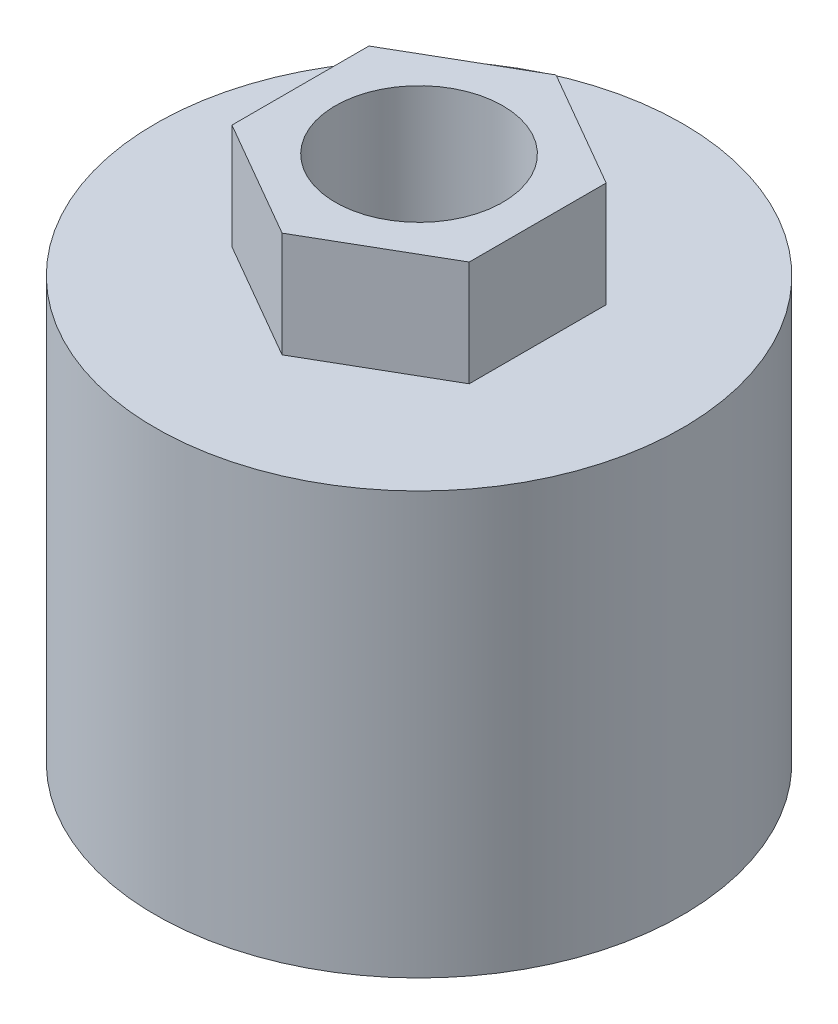
SolidWorks part; units mm, degrees
ref_plane "Front Plane" through (0, 0, 0) normal (0, 0, 1) x (1, 0, 0)
ref_plane "Top Plane" through (0, 0, 0) normal (0, 1, 0) x (1, 0, 0)
ref_plane "Right Plane" through (0, 0, 0) normal (1, 0, 0) x (0, 0, -1)
sketch "Sketch1" plane through (0, 0, 0) normal (0, 0, 1) x (1, 0, 0)
  line L3 (15.875, 0) -> (15.875, 25.4)
  line L7 (0, 0) -> (0, 63.6042) construction
  line L8 (5.0419, 0) -> (5.0419, 25.4)
  line L9 (5.0419, 0) -> (15.875, 0)
  line L10 (0, 0) -> (48.1845, 0) construction
  line L11 (5.0419, 25.4) -> (15.875, 25.4)
  point P1 (25.4, 24.9189)
  dimension "D1" = 10.0838
  dimension "D3" = 31.75
  dimension "D7" = 25.4
revolve "Revolve1" add sketch "Sketch1" angle 360 about L7
sketch "Sketch3" plane through (0, 0, 0) normal (0, -1, 0) x (1, 0, 0)
  line L0 (0, 0) -> (0, 8.7988) construction
  line L1 (7.62, -4.3994) -> (7.62, 4.3994)
  line L2 (7.62, 4.3994) -> (0, 8.7988)
  line L3 (0, 8.7988) -> (-7.62, 4.3994)
  line L4 (-7.62, 4.3994) -> (-7.62, -4.3994)
  line L5 (-7.62, -4.3994) -> (0, -8.7988)
  line L6 (0, -8.7988) -> (7.62, -4.3994)
  circle A0 centre (0, 0) radius 7.62 construction
  dimension "D1" = 15.24
extrude "Cut-Extrude1" cut sketch "Sketch3" against normal blind 9.525
sketch "Sketch4" plane through (0, 25.4, 0) normal (0, 1, 0) x (1, 0, 0)
  line L0 (0, 0) -> (0, 8.2489) construction
  line L1 (0, 8.2489) -> (-7.1437, 4.1244)
  line L2 (-7.1437, 4.1244) -> (-7.1437, -4.1244)
  line L3 (-7.1437, -4.1244) -> (0, -8.2489)
  line L4 (0, -8.2489) -> (7.1437, -4.1244)
  line L5 (7.1437, -4.1244) -> (7.1437, 4.1244)
  line L6 (7.1437, 4.1244) -> (0, 8.2489)
  circle A0 centre (0, 0) radius 7.1437 construction
  dimension "D1" = 14.2875
extrude "Boss-Extrude1" add sketch "Sketch4" along normal blind 6.35
sketch "Sketch5" plane through (0, 25.4, 0) normal (0, -1, 0) x (1, 0, 0)
  circle A1 centre (0, 0) radius 5.0419
  circle A2 centre (0, 0) radius 5.0419
  dimension "D1" = 0
extrude "Cut-Extrude2" cut sketch "Sketch5" against normal through all
